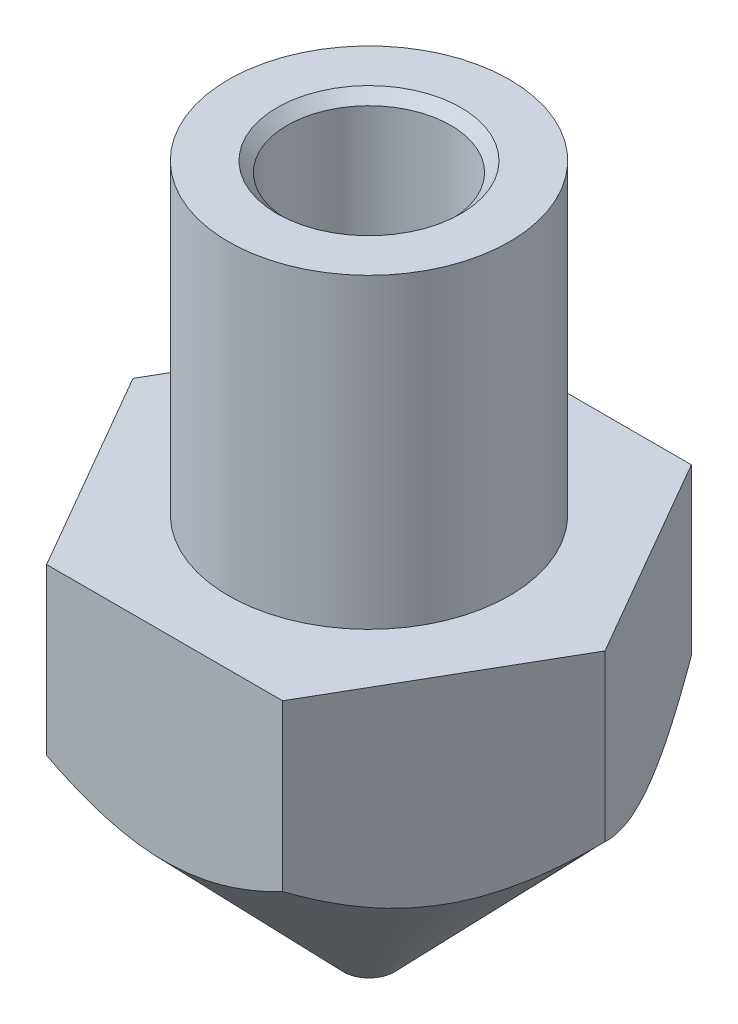
SolidWorks part; units mm, degrees
material "acero"
ref_plane "Alzado" through (0, 0, 0) normal (0, 0, 1) x (1, 0, 0)
ref_plane "Planta" through (0, 0, 0) normal (0, 1, 0) x (1, 0, 0)
ref_plane "Vista lateral" through (0, 0, 0) normal (1, 0, 0) x (0, 0, -1)
sketch "Croquis1" plane through (0, 0, 0) normal (0, 0, 1) x (1, 0, 0)
  line L0 (0.2, 0) -> (0.5, 0)
  line L1 (0.5, 0) -> (7.7427, 7.5)
  line L3 (7.7427, 7.5) -> (2.75, 7.5)
  line L4 (2.75, 7.5) -> (2.75, 13.5)
  line L5 (2.75, 13.5) -> (1.6, 13.5)
  line L6 (1.6, 13.5) -> (1.6, 2.4249)
  line L7 (1.6, 2.4249) -> (0.2, 0)
  line L8 (0, 0) -> (0, 18.2336) construction
  dimension "D1" = 0.2
  dimension "D2" = 0.5
  dimension "D3" = 1.6
  dimension "D4" = 2.75
  dimension "D5" = 13.5
  dimension "D6" = 6
  dimension "D7" = 30
  dimension "D8" = 44
revolve "Revolución1" add sketch "Croquis1" angle 360 about L8
sketch "Croquis2" plane through (0, 7.5, 0) normal (0, 1, 0) x (1, 0, 0)
  line L1 (2.3094, 4) -> (-2.3094, 4)
  line L2 (-2.3094, 4) -> (-4.6188, 0)
  line L3 (-4.6188, 0) -> (-2.3094, -4)
  line L4 (-2.3094, -4) -> (2.3094, -4)
  line L5 (2.3094, -4) -> (4.6188, 0)
  line L6 (4.6188, 0) -> (2.3094, 4)
  circle A0 centre (0, 0) radius 4 construction
  circle A2 centre (0, 0) radius 7.7427 construction
  circle A3 centre (0, 0) radius 7.7427
  dimension "D1" = 8
extrude "Cortar-Extruir1" cut sketch "Croquis2" against normal through all
chamfer "Chaflán1" distance 0.2 angle 45 1 edges at (0, 13.5, -1.6)
